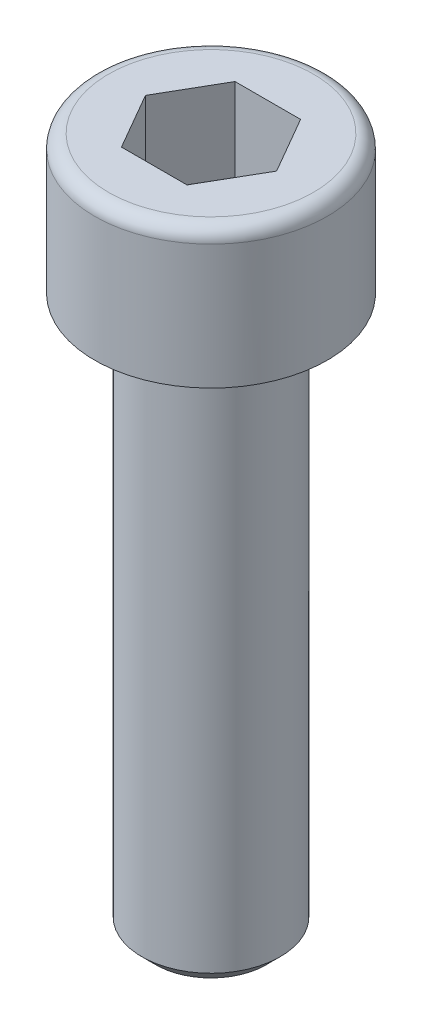
SolidWorks part; units mm, degrees
ref_plane "Plan de face" through (0, 0, 0) normal (0, 0, 1) x (1, 0, 0)
ref_plane "Plan de dessus" through (0, 0, 0) normal (0, 1, 0) x (1, 0, 0)
ref_plane "Plan de droite" through (0, 0, 0) normal (1, 0, 0) x (0, 0, -1)
sketch "Esquisse1" plane through (0, 0, 0) normal (0, 0, 1) x (1, 0, 0)
  line L0 (4.2, 5) -> (0, 5)
  line L1 (0, 5) -> (0, 0)
  line L2 (0, 0) -> (4.2, 0)
  line L3 (4.2, 0) -> (4.2, 5)
  line L4 (0, 5) -> (0, 0) construction
revolve "Révolution1" add sketch "Esquisse1" angle 360 about L4
sketch "Esquisse2" plane through (0, 0, 0) normal (0, -1, 0) x (1, 0, 0)
  circle A0 centre (0, 0) radius 2.5
extrude "Boss.-Extru.1" add sketch "Esquisse2" along normal blind 20
sketch "Esquisse3" plane through (0, 5, 0) normal (0, 1, 0) x (-1, 0, 0)
  line L0 (1.1836, 2.05) -> (-1.1836, 2.05)
  line L1 (-1.1836, 2.05) -> (-2.3671, 0)
  line L2 (-2.3671, 0) -> (-1.1836, -2.05)
  line L3 (-1.1836, -2.05) -> (1.1836, -2.05)
  line L4 (1.1836, -2.05) -> (2.3671, 0)
  line L5 (2.3671, 0) -> (1.1836, 2.05)
extrude "Enlèv. mat.-Extru.1" cut sketch "Esquisse3" against normal blind 3
chamfer "Chanfrein1" distance 0.5 angle 45 1 edges at (0, -20, -2.5)
fillet "Congé1" radius 0.5 1 edges at (0, 5, -4.2)
